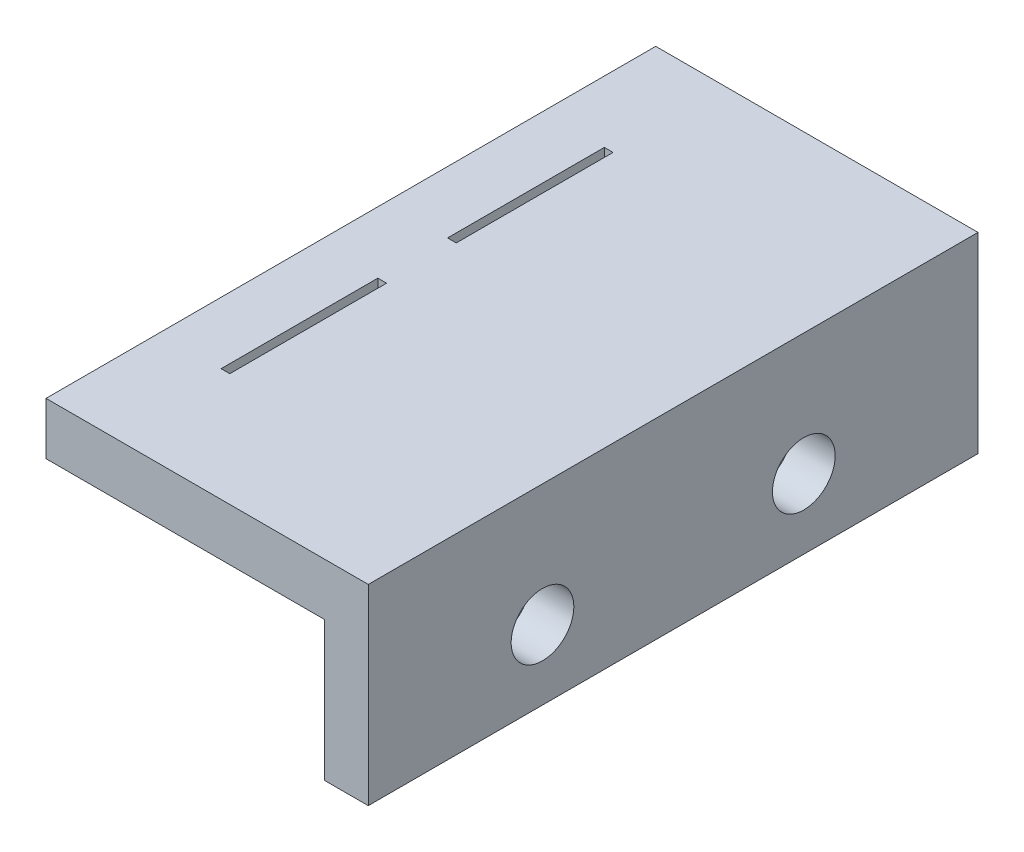
SolidWorks part; units mm, degrees
ref_plane "前视基准面" through (0, 0, 0) normal (0, 0, 1) x (1, 0, 0)
ref_plane "上视基准面" through (0, 0, 0) normal (0, 1, 0) x (1, 0, 0)
ref_plane "右视基准面" through (0, 0, 0) normal (1, 0, 0) x (0, 0, -1)
sketch "Sketch1" plane through (0, 0, 0) normal (0, 1, 0) x (1, 0, 0)
  line L1 (0, 0) -> (70.4, 0)
  line L2 (0, 0) -> (0, 2)
  line L3 (0, 2) -> (70.4, 2)
  line L4 (70.4, 0) -> (70.4, 2)
  dimension "D1" = 70.4
  dimension "D2" = 2
extrude "Boss-Extrude2" add sketch "Sketch1" along normal blind 10
sketch "Sketch2" plane through (0, 10, 0) normal (0, 1, 0) x (1, 0, 0)
  line L1 (0, 2) -> (2, 2)
  line L2 (0, 2) -> (0, 57)
  line L3 (0, 57) -> (2, 57)
  line L4 (2, 2) -> (2, 57)
  line L5 (70.4, 2) -> (68.4, 2)
  line L6 (70.4, 2) -> (70.4, 57)
  line L7 (70.4, 57) -> (68.4, 57)
  line L8 (68.4, 2) -> (68.4, 57)
  dimension "D1" = 55
  dimension "D2" = 2
  dimension "D3" = 2
extrude "Boss-Extrude3" add sketch "Sketch2" against normal blind 10
sketch "Sketch3" plane through (0, 0, 0) normal (0, 0, 1) x (1, 0, 0)
  line L0 (35.2, 0) -> (35.2, 21.6902) construction
  line L1 (0, 0) -> (70.4, 0) construction
  line L2 (0, 10) -> (70.4, 10) construction
  line L3 (25.7, 10) -> (44.7, 10)
  line L4 (25.7, 10) -> (25.7, 13)
  line L5 (25.7, 13) -> (44.7, 13)
  line L6 (44.7, 10) -> (44.7, 13)
  dimension "D1" = 9.5
  dimension "D2" = 9.5
  dimension "D3" = 3
extrude "Boss-Extrude4" add sketch "Sketch3" against normal blind 2
sketch "Sketch4" plane through (0, 0, 0) normal (0, 0, 1) x (1, 0, 0)
  line L0 (35.2, 0) -> (35.2, 21.4055) construction
  line L1 (0, 0) -> (70.4, 0) construction
  line L3 (27.7, 0) -> (42.7, 0)
  line L4 (27.7, 0) -> (27.7, 10)
  line L5 (27.7, 10) -> (42.7, 10)
  line L6 (42.7, 0) -> (42.7, 10)
  dimension "D1" = 10
  dimension "D2" = 7.5
  dimension "D3" = 7.5
extrude "Cut-Extrude2" cut sketch "Sketch4" against normal blind 2
sketch "Sketch5" plane through (25.7, 0, 0) normal (-1, 0, 0) x (0, 0, 1)
  line L1 (-2, 13) -> (0, 13)
  line L2 (-2, 13) -> (-2, 10)
  line L3 (-2, 10) -> (0, 10)
  line L4 (0, 13) -> (0, 10)
extrude "Boss-Extrude5" add sketch "Sketch5" along normal blind 1
sketch "Sketch6" plane through (44.7, 0, 0) normal (1, 0, 0) x (0, 0, -1)
  line L1 (0, 13) -> (2, 13)
  line L2 (0, 13) -> (0, 10)
  line L3 (0, 10) -> (2, 10)
  line L4 (2, 13) -> (2, 10)
extrude "Boss-Extrude6" add sketch "Sketch6" along normal blind 1
sketch "Sketch7" plane through (0, 0, 0) normal (-1, 0, 0) x (0, 0, 1)
  line L0 (0, 10) -> (0, 0) construction
  line L1 (-57, 0) -> (0, 0)
  line L2 (-57, 0) -> (-57, 2)
  line L3 (-57, 2) -> (0, 2)
  line L4 (0, 0) -> (0, 2)
  dimension "D1" = 2
extrude "Boss-Extrude7" add sketch "Sketch7" along normal blind 6.6
sketch "Sketch8" plane through (70.4, 0, 0) normal (1, 0, 0) x (0, 0, -1)
  line L0 (57, 0) -> (57, 10) construction
  line L1 (0, 0) -> (57, 0)
  line L2 (0, 0) -> (0, 2)
  line L3 (0, 2) -> (57, 2)
  line L4 (57, 0) -> (57, 2)
  dimension "D1" = 2
extrude "Boss-Extrude8" add sketch "Sketch8" along normal blind 6.6
sketch "Sketch10" plane through (0, 0, -57) normal (0, 0, -1) x (-1, 0, 0)
  line L0 (-2, 10) -> (-2, 0)
  line L1 (-2, 0) -> (6.6, 0)
  line L2 (6.6, 0) -> (6.6, 2)
  line L3 (6.6, 2) -> (0, 2)
  line L4 (0, 2) -> (0, 10)
  line L5 (0, 10) -> (-2, 10)
  line L6 (-77, 0) -> (-68.4, 0)
  line L7 (-68.4, 0) -> (-68.4, 10)
  line L8 (-68.4, 10) -> (-70.4, 10)
  line L9 (-70.4, 10) -> (-70.4, 2)
  line L10 (-70.4, 2) -> (-77, 2)
  line L11 (-77, 2) -> (-77, 0)
extrude "Boss-Extrude9" add sketch "Sketch10" along normal blind 5
sketch "Sketch12" plane through (0, 10, 0) normal (0, 1, 0) x (1, 0, 0)
  line L0 (0, 0) -> (0, 62) construction
  line L1 (0, 57) -> (2, 57)
  line L2 (0, 57) -> (0, 17)
  line L3 (0, 17) -> (2, 17)
  line L4 (2, 57) -> (2, 17)
  line L5 (2, 2) -> (2, 62) construction
  line L6 (0, 62) -> (2, 62) construction
  line L7 (68.4, 62) -> (68.4, 2) construction
  line L8 (68.4, 57) -> (70.4, 57)
  line L9 (68.4, 57) -> (68.4, 27)
  line L10 (68.4, 27) -> (70.4, 27)
  line L11 (70.4, 57) -> (70.4, 27)
  line L12 (70.4, 62) -> (70.4, 0) construction
  line L13 (68.4, 62) -> (70.4, 62) construction
  line L15 (2, 62) -> (0, 62)
  line L16 (2, 62) -> (2, 57)
  line L17 (2, 57) -> (0, 57)
  line L18 (0, 62) -> (0, 57)
  line L19 (70.4, 62) -> (68.4, 62)
  line L20 (70.4, 62) -> (70.4, 57)
  line L21 (70.4, 57) -> (68.4, 57)
  line L22 (68.4, 62) -> (68.4, 57)
  line M4 (2, 2) -> (2, 62)
  line M5 (2, 62) -> (0, 62)
  line M6 (0, 62) -> (0, 0)
  dimension "D1" = 5
  dimension "D2" = 40
  dimension "D3" = 5
  dimension "D4" = 30
extrude "Boss-Extrude10" add sketch "Sketch12" along normal blind 20 contours L1 M6 M4 M5 | L3 L1 M6 M4 | L11 L8 L9 L10 | L19 L22 L8 L20
sketch "Sketch13" plane through (0, 30, 0) normal (0, 1, 0) x (1, 0, 0)
  line L0 (35.2, 2) -> (35.2, 63.9637) construction
  line L1 (45.7, 2) -> (24.7, 2) construction
  line L2 (0, 17) -> (35.2, 17)
  line L3 (35.2, 17) -> (35.2, 27)
  line L4 (35.2, 27) -> (70.4, 27)
  line L5 (70.4, 27) -> (70.4, 62)
  line L6 (70.4, 62) -> (0, 62)
  line L7 (0, 62) -> (0, 17)
extrude "Boss-Extrude11" add sketch "Sketch13" along normal blind 3
sketch "Sketch14" plane through (0, 33, 0) normal (0, 1, 0) x (1, 0, 0)
  line L0 (35.2, 62) -> (35.2, 11.7147) construction
  line L1 (70.4, 62) -> (0, 62) construction
  line L2 (10.2, 62) -> (10.2, 11.7147) construction
  line L3 (60.2, 62) -> (60.2, 11.7147) construction
  line L4 (10.2, 57) -> (60.2, 57) construction
  line L5 (11.7, 57) -> (11.7, 17) construction
  line L6 (0, 17) -> (35.2, 17) construction
  line L7 (58.2, 57) -> (58.2, 27) construction
  line L8 (35.2, 27) -> (70.4, 27) construction
  line L10 (11.45, 55.5) -> (11.95, 55.5)
  line L11 (11.45, 55.5) -> (11.45, 46.5)
  line L12 (11.45, 46.5) -> (11.95, 46.5)
  line L13 (11.95, 55.5) -> (11.95, 46.5)
  line L14 (11.45, 42.5) -> (11.95, 42.5)
  line L15 (11.45, 42.5) -> (11.45, 33.5)
  line L16 (11.45, 33.5) -> (11.95, 33.5)
  line L17 (11.95, 42.5) -> (11.95, 33.5)
  line L18 (11.45, 30) -> (11.95, 30)
  line L19 (11.45, 30) -> (11.45, 21)
  line L20 (11.45, 21) -> (11.95, 21)
  line L21 (11.95, 30) -> (11.95, 21)
  line L22 (57.95, 55.5) -> (58.45, 55.5)
  line L23 (57.95, 55.5) -> (57.95, 46.5)
  line L24 (57.95, 46.5) -> (58.45, 46.5)
  line L25 (58.45, 55.5) -> (58.45, 46.5)
  line L26 (57.95, 42.5) -> (58.45, 42.5)
  line L27 (57.95, 42.5) -> (57.95, 33.5)
  line L28 (57.95, 33.5) -> (58.45, 33.5)
  line L29 (58.45, 42.5) -> (58.45, 33.5)
  dimension "D1" = 25
  dimension "D2" = 25
  dimension "D3" = 5
  dimension "D4" = 1.5
  dimension "D5" = 2
  dimension "D6" = 0.5
  dimension "D7" = 0.25
  dimension "D8" = 1.5
  dimension "D9" = 9
  dimension "D10" = 4
  dimension "D11" = 9
  dimension "D12" = 9
  dimension "D13" = 3.5
  dimension "D14" = 1.5
  dimension "D15" = 0.25
  dimension "D16" = 0.25
  dimension "D17" = 9
  dimension "D18" = 4
extrude "Cut-Extrude3" cut sketch "Sketch14" against normal blind 3
sketch "Sketch15" plane through (0, 33, 0) normal (0, 1, 0) x (1, 0, 0)
  line L0 (70.4, 62) -> (0, 62) construction
  line L1 (16, 62) -> (54.4, 62)
  line L2 (16, 62) -> (16, 17)
  line L3 (16, 17) -> (54.4, 17)
  line L4 (54.4, 62) -> (54.4, 17)
  line L5 (0, 62) -> (0, 17) construction
  line L6 (70.4, 62) -> (70.4, 0) construction
  dimension "D1" = 16
  dimension "D2" = 16
extrude "Cut-Extrude4" cut sketch "Sketch15" against normal blind 3
sketch "Sketch16" plane through (0, 0, 0) normal (0, 0, 1) x (1, 0, 0)
  line L0 (-6.6, 0) -> (27.7, 0)
  line L1 (27.7, 0) -> (27.7, 10)
  line L2 (27.7, 10) -> (42.7, 10)
  line L3 (42.7, 10) -> (42.7, 0)
  line L4 (42.7, 0) -> (77, 0)
  line L5 (77, 0) -> (77, 2)
  line L6 (77, 2) -> (70.4, 2)
  line L7 (70.4, 2) -> (70.4, 10)
  line L8 (70.4, 10) -> (45.7, 10)
  line L9 (45.7, 10) -> (45.7, 13)
  line L10 (45.7, 13) -> (24.7, 13)
  line L11 (24.7, 13) -> (24.7, 10)
  line L12 (24.7, 10) -> (0, 10)
  line L13 (0, 10) -> (0, 2)
  line L14 (0, 2) -> (-6.6, 2)
  line L15 (-6.6, 2) -> (-6.6, 0)
extrude "Boss-Extrude12" add sketch "Sketch16" along normal blind 0.5
sketch "Sketch17" plane through (0, 2, 0) normal (0, 1, 0) x (1, 0, 0)
  line L0 (-3.3, -0.5) -> (-3.3, 64.6995) construction
  line L1 (0, -0.5) -> (-6.6, -0.5) construction
  line L2 (73.7, -0.5) -> (73.7, 65.8086) construction
  line L3 (77, -0.5) -> (70.4, -0.5) construction
  line L4 (-6.6, 62) -> (0, 62) construction
  line L5 (70.4, 62) -> (77, 62) construction
  line L6 (0, 17) -> (16, 17) construction
  line L7 (-4.8, 17) -> (-1.8, 17)
  line L8 (-4.8, 17) -> (-4.8, 12)
  line L9 (-4.8, 12) -> (-1.8, 12)
  line L10 (-1.8, 17) -> (-1.8, 12)
  line L12 (72.2, 17) -> (75.2, 17)
  line L13 (72.2, 17) -> (72.2, 12)
  line L14 (72.2, 12) -> (75.2, 12)
  line L15 (75.2, 17) -> (75.2, 12)
  circle A0 centre (-3.3, 55) radius 1.8
  circle A1 centre (73.7, 55) radius 1.8
  circle A2 centre (-3.3, 6.5) radius 1.8
  circle A3 centre (73.7, 6.5) radius 1.8
  circle A4 centre (-3.3, 30.75) radius 1.8
  circle A5 centre (73.7, 30.75) radius 1.8
  dimension "D1" = 3.6
  dimension "D2" = 3.6
  dimension "D3" = 3.6
  dimension "D4" = 3.6
  dimension "D9" = 3.6
  dimension "D10" = 3.6
  dimension "D5" = 7
  dimension "D6" = 7
  dimension "D7" = 7
  dimension "D8" = 7
  dimension "D11" = 1.5
  dimension "D12" = 1.5
  dimension "D13" = 5
  dimension "D14" = 0
  dimension "D15" = 1.5
  dimension "D16" = 1.5
extrude "Cut-Extrude6" cut sketch "Sketch17" against normal blind 3
sketch "Sketch18" plane through (0, 0, 0) normal (-1, 0, 0) x (0, 0, 1)
  line L1 (-62, 33) -> (14.2088, 33)
  line L2 (-62, 33) -> (-62, -26.7975)
  line L3 (-62, -26.7975) -> (14.2088, -26.7975)
  line L4 (14.2088, 33) -> (14.2088, -26.7975)
extrude "Cut-Extrude7" cut sketch "Sketch18" against normal blind 51 and the other way blind 71
sketch "Sketch19" plane through (68.4, 0, 0) normal (-1, 0, 0) x (0, 0, 1)
  line L1 (-62, 30) -> (18.2301, 30)
  line L2 (-62, 30) -> (-62, -3.8511)
  line L3 (-62, -3.8511) -> (18.2301, -3.8511)
  line L4 (18.2301, 30) -> (18.2301, -3.8511)
extrude "Cut-Extrude8" cut sketch "Sketch19" against normal blind 25 and the other way blind 87
sketch "Sketch20" plane through (70.4, 0, 0) normal (1, 0, 0) x (0, 0, -1)
  line L1 (27, 33) -> (62, 33)
  line L2 (27, 33) -> (27, 30)
  line L3 (27, 30) -> (62, 30)
  line L4 (62, 33) -> (62, 30)
extrude "Boss-Extrude13" add sketch "Sketch20" along normal blind 2.5
sketch "Sketch21" plane through (0, 30, 0) normal (0, -1, 0) x (1, 0, 0)
  line L0 (72.9, -62) -> (54.4, -62) construction
  line L1 (72.9, -27) -> (70.4, -27)
  line L2 (72.9, -27) -> (72.9, -62)
  line L3 (72.9, -62) -> (70.4, -62)
  line L4 (70.4, -27) -> (70.4, -62)
  dimension "D1" = 2.5
extrude "Boss-Extrude14" add sketch "Sketch21" along normal blind 8
sketch "Sketch22" plane through (70.4, 0, 0) normal (-1, 0, 0) x (0, 0, 1)
  line L0 (-62, 26) -> (-23.4504, 26) construction
  line L1 (-62, 22) -> (-62, 30) construction
  line L2 (-27, 22) -> (-27, 30) construction
  circle A0 centre (-52, 26) radius 1.8
  circle A1 centre (-37, 26) radius 1.8
  dimension "D1" = 3.6
  dimension "D2" = 3.6
  dimension "D3" = 10
  dimension "D4" = 10
extrude "Cut-Extrude10" cut sketch "Sketch22" against normal blind 10 contours A1 | A0
